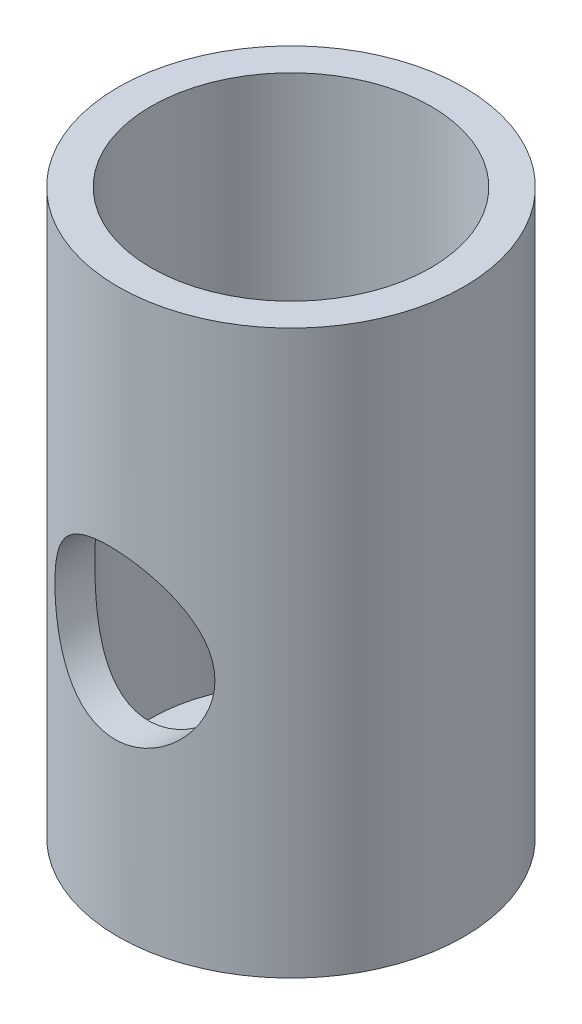
SolidWorks part; units mm, degrees
ref_plane "Plan de face" through (0, 0, 0) normal (0, 0, 1) x (1, 0, 0)
ref_plane "Plan de dessus" through (0, 0, 0) normal (0, 1, 0) x (1, 0, 0)
ref_plane "Plan de droite" through (0, 0, 0) normal (1, 0, 0) x (0, 0, -1)
sketch "Esquisse1" plane through (0, 0, 0) normal (0, 0, 1) x (1, 0, 0)
  line L0 (0, 8.3462) -> (0, -11.3462) construction
  line L1 (-4.25, 5.7692) -> (-5.25, 5.7692)
  line L2 (-5.25, 5.7692) -> (-5.25, -11.3287)
  line L3 (-4.25, -10.3287) -> (0, -10.3287)
  line L4 (-4.25, -10.3287) -> (-4.25, 5.7692)
  line L5 (0, -10.3287) -> (0, -11.3287)
  line L6 (0, -11.3287) -> (-5.25, -11.3287)
  point P5 (-2.125, -10.3287)
  dimension "D1" = 1
  dimension "D2" = 4.25
  dimension "D3" = 1
revolve "Révolution1" add sketch "Esquisse1" angle 360 about L0
hole_wizard "Trou taraudé #0-801" positions "Esquisse3D2" profile "Esquisse2" tap size "#0-80" standard "PCS"
sketch3d "Esquisse3D2"
  point P0 (0, 0, 0)
  point P3 (-0.1432, -3.6868, 5.248)
sketch "Esquisse2" plane through (-0.1432, -3.6868, 5.248) normal (0, 1, 0) x (0.9996, 0, 0.0273)
  line L0 (0, 0) -> (0, 10.6413)
  line L1 (0, 10.6413) -> (2.5, 10.6413)
  line L2 (2.5, 10.6413) -> (2.5, 0)
  line L5 (2.5, 0) -> (0, 0)
  line L11 (0, -6.35) -> (0, 107.95) construction
  dimension "Diamètre du trou pour taraudage jusqu'au prochain" = 5
  dimension "Profondeur du trou pour taraudage jusqu'au prochain" = 10.6413
cosmetic thread "Filetage de perçage1" parameters "D2"=8
